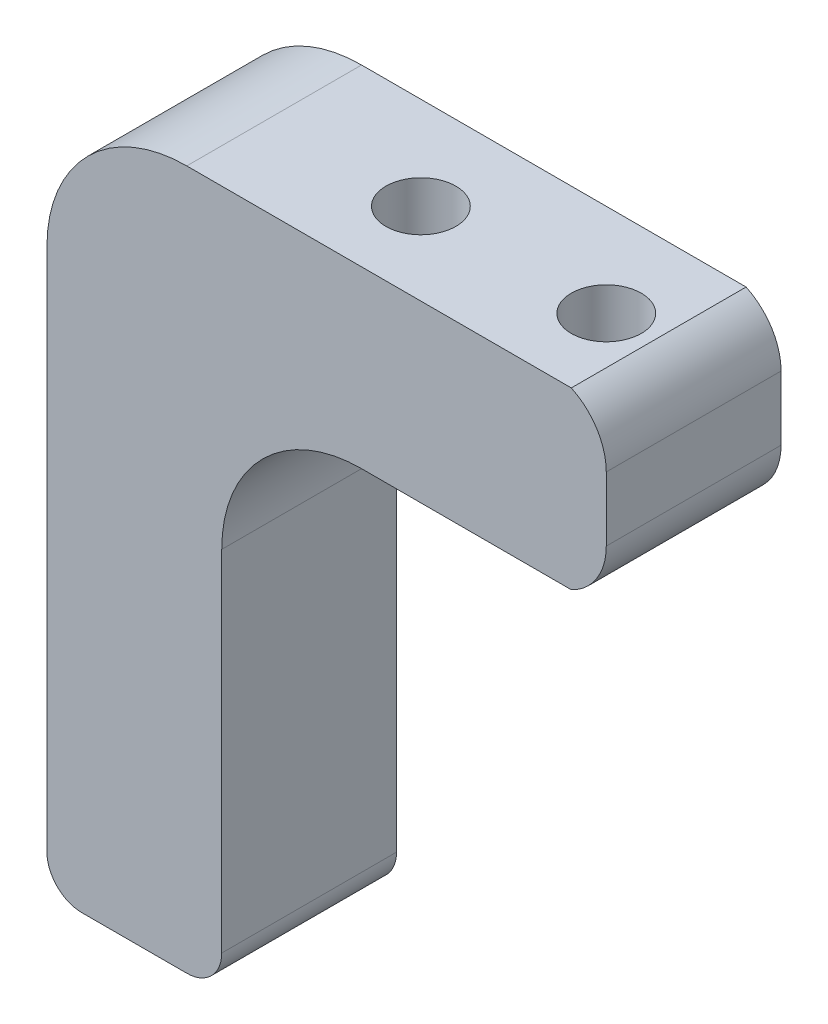
SolidWorks part; units mm, degrees
ref_plane "Alzado" through (0, 0, 0) normal (0, 0, 1) x (1, 0, 0)
ref_plane "Planta" through (0, 0, 0) normal (0, 1, 0) x (1, 0, 0)
ref_plane "Vista lateral" through (0, 0, 0) normal (1, 0, 0) x (0, 0, -1)
sketch "Croquis1" plane through (0, 0, 0) normal (0, 0, 1) x (1, 0, 0)
  line L0 (8, 40) -> (36, 40) construction
  line L5 (40, 36) -> (40, 34) construction
  line L6 (36, 30) -> (18, 30) construction
  line L11 (0, 0) -> (11.2789, 0) construction
  line L12 (0, 0) -> (0, -5.6644) construction
  line L13 (2, 0) -> (8, 0)
  line L14 (0, 32) -> (0, 2) construction
  line L15 (10, 22) -> (10, 2) construction
  line L16 (8, 0) -> (2, 0) construction
  line L18 (10, 2) -> (10, 22)
  line L19 (18, 30) -> (36, 30)
  line L20 (40, 36) -> (40, 34)
  line L21 (8, 40) -> (36, 40)
  line L22 (0, 32) -> (0, 2)
  arc A2 (36, 30) -> (40, 34) centre (36, 34) ccw
  arc A3 (40, 36) -> (36, 40) centre (36, 36) ccw
  arc A12 (2, 0) -> (0, 2) centre (2, 2) cw
  arc A13 (8, 0) -> (10, 2) centre (8, 2) ccw
  arc A16 (18, 30) -> (10, 22) centre (18, 22) ccw
  arc A17 (0, 32) -> (8, 40) centre (8, 32) cw
  point P36 (10, 0)
  dimension "D1" = 8
  dimension "D6" = 4
  dimension "D5" = 40
  dimension "D4" = 2
  dimension "D2" = 10
  dimension "D3" = 10
  dimension "D7" = 40
extrude "Saliente-Extruir1" add sketch "Croquis1" along normal blind 10
sketch "Croquis2" plane through (0, 40, 0) normal (0, 1, 0) x (1, 0, 0)
  line L0 (27.3033, -5.3033) -> (16.6967, -5.3033) construction
  line L4 (16.6967, -5.3033) -> (22, 0) construction
  line L5 (22, 0) -> (27.3033, -5.3033) construction
  line L8 (36, 0) -> (8, 0) construction
  circle A0 centre (16.6967, -5.3033) radius 1.75 construction
  circle A1 centre (27.3033, -5.3033) radius 1.75 construction
  circle A2 centre (16.6967, -5.3033) radius 2
  circle A3 centre (27.3033, -5.3033) radius 2
  dimension "D1" = 3.5
  dimension "D2" = 3.5
  dimension "D3" = 7.5
  dimension "D4" = 7.5
  dimension "D5" = 90
  dimension "D6" = 0.25
extrude "Cortar-Extruir2" cut sketch "Croquis2" against normal blind 30 contours A2 | A3
sketch "Croquis3" plane through (0, 0, 10) normal (0, 0, 1) x (1, 0, 0)
  line L0 (32, 36.8377) -> (32, 33.1623)
  line L1 (30, 40) -> (36, 40)
  line L2 (36, 30) -> (30, 30)
  line L6 (18, 30) -> (36, 30)
  line L7 (40, 34) -> (40, 36)
  line L8 (36, 40) -> (8, 40)
  line L9 (0, 32) -> (0, 2)
  line L10 (2, 0) -> (8, 0)
  line L11 (10, 2) -> (10, 22)
  line L13 (40, 34) -> (40, 36)
  arc A0 (30, 30) -> (32, 33.1623) centre (28.5, 33.1623) ccw
  arc A1 (32, 36.8377) -> (30, 40) centre (28.5, 36.8377) ccw
  arc A6 (18, 30) -> (10, 22) centre (18, 22) ccw
  arc A7 (36, 30) -> (40, 34) centre (36, 34) ccw
  arc A8 (40, 36) -> (36, 40) centre (36, 36) ccw
  arc A9 (8, 40) -> (0, 32) centre (8, 32) ccw
  arc A10 (0, 2) -> (2, 0) centre (2, 2) ccw
  arc A11 (8, 0) -> (10, 2) centre (8, 2) ccw
  arc A13 (36, 30) -> (40, 34) centre (36, 34) ccw
  arc A14 (40, 36) -> (36, 40) centre (36, 36) ccw
  dimension "D2" = 3.5
  dimension "D3" = 6
  dimension "D4" = 6
  dimension "D5" = 8
  dimension "D1" = 0
extrude "Cortar-Extruir3" cut sketch "Croquis3" against normal blind 10
